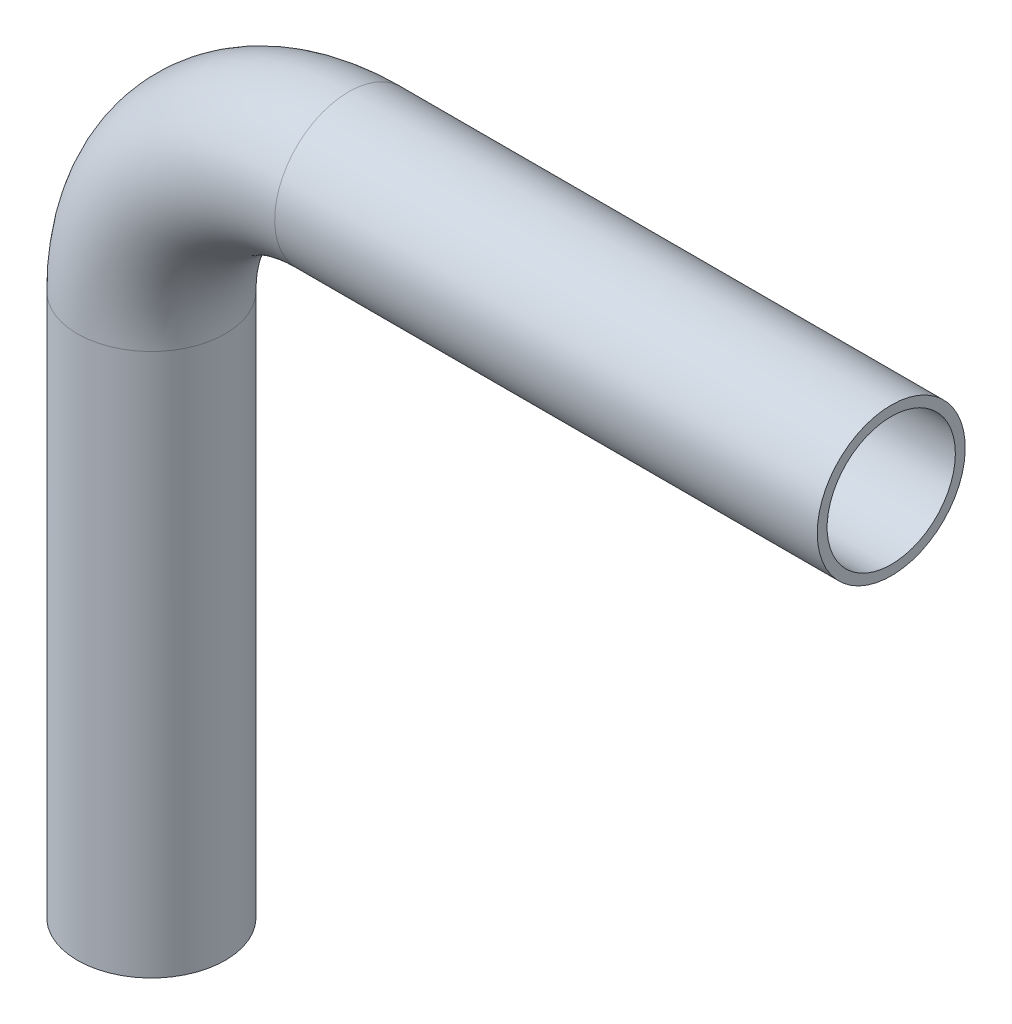
SolidWorks part; units mm, degrees
ref_plane "Plano frontal" through (0, 0, 0) normal (0, 0, 1) x (1, 0, 0)
ref_plane "Plano superior" through (0, 0, 0) normal (0, 1, 0) x (1, 0, 0)
ref_plane "Plano direito" through (0, 0, 0) normal (1, 0, 0) x (0, 0, -1)
sketch "Esboço1" plane through (0, 0, 0) normal (0, 0, 1) x (1, 0, 0)
  line L0 (0, 0) -> (0, 110)
  line L1 (40, 150) -> (150, 150)
  arc A0 (40, 150) -> (0, 110) centre (40, 110) ccw
  point P6 (0, 150)
  dimension "D3" = 40
  dimension "D1" = 150
  dimension "D2" = 150
sketch "Esboço2" plane through (0, 0, 0) normal (0, 1, 0) x (1, 0, 0)
  circle A0 centre (0, 0) radius 15
  dimension "D1" = 30
sweep "Varredura1" add profiles "Esboço2" path "Esboço1"
shell "Casca1" thickness 2
